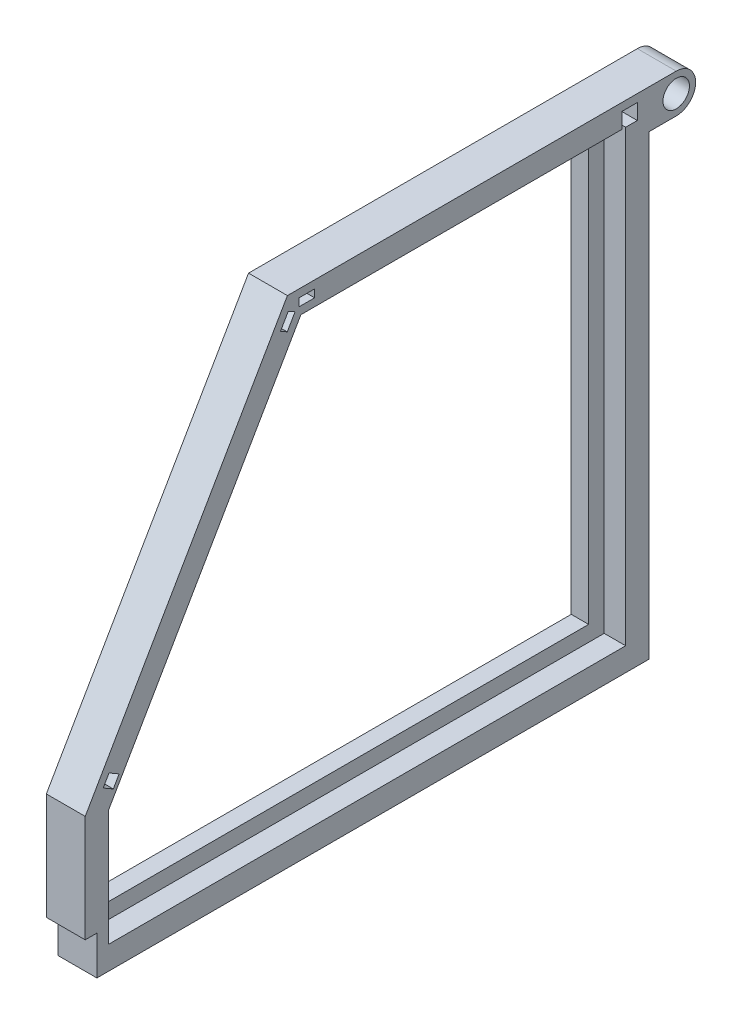
SolidWorks part; units mm, degrees
ref_plane "Front Plane" through (0, 0, 0) normal (0, 0, 1) x (1, 0, 0)
ref_plane "Top Plane" through (0, 0, 0) normal (0, 1, 0) x (1, 0, 0)
ref_plane "Right Plane" through (0, 0, 0) normal (1, 0, 0) x (0, 0, -1)
sketch "Sketch1" plane through (0, 0, 0) normal (1, 0, 0) x (0, 0, -1)
  line L0 (-36.25, 0.2437) -> (36.25, 0.2437)
  line L1 (36.25, 0.2437) -> (36.25, 58.9937)
  line L2 (36.25, 58.9937) -> (39.75, 58.9937)
  line L3 (39.75, 58.9937) -> (39.75, 61.4937) construction
  line L4 (39.75, 63.9937) -> (36.25, 63.9937)
  line L5 (36.25, 63.9937) -> (-10.25, 63.9937)
  line L6 (-36.25, 0.2437) -> (-36.25, 18.9937)
  line L7 (-36.25, 18.9937) -> (-10.25, 63.9937)
  line L8 (36.25, 0.2437) -> (31.25, 0.2437) construction
  line L9 (31.25, 0.2437) -> (31.25, 5.2437) construction
  line L12 (31.25, 5.2437) -> (-31.25, 5.2437)
  line L19 (31.25, 63.9937) -> (31.25, 58.9937) construction
  line L20 (31.25, 5.2437) -> (31.25, 58.9937)
  line L23 (-23.25, 41.4937) -> (-18.9207, 38.9924) construction
  line L24 (-18.9207, 38.9924) -> (-7.3643, 58.9937)
  line L27 (-18.9207, 38.9924) -> (-31.25, 17.6531)
  line L28 (-31.25, 5.2437) -> (-31.25, 17.6531)
  line L29 (-7.3643, 58.9937) -> (31.25, 58.9937)
  arc A0 (39.75, 58.9937) -> (39.75, 63.9937) centre (39.75, 61.4937) ccw
  point P3 (0, 0.2437)
extrude "Boss-Extrude1" add sketch "Sketch1" along normal blind 5
sketch "Sketch2" plane through (0, 0, 0) normal (-1, 0, 0) x (0, 0, 1)
  line L0 (-42.25, 61.4937) -> (-39.75, 61.4937) construction
hole_wizard "CSK for M3 Flat Head Machine Screw1" positions "Sketch3" profile "Sketch4" countersink size "M3" standard "ANSI Metric"
sketch "Sketch3" plane through (0, 0, 0) normal (-1, 0, 0) x (0, 0, 1)
  point P0 (-39.75, 61.4937)
sketch "Sketch4" plane through (0, 61.4937, -39.75) normal (0, 1, 0) x (0, 0, 1)
  line L0 (0, 0) -> (0, 11.0215)
  line L1 (0, 11.0215) -> (1.7, 10)
  line L2 (1.7, 10) -> (1.7, 0.4)
  line L3 (1.7, 0.4) -> (2.1, 0)
  line L5 (2.1, 0) -> (0, 0)
  line L6 (-1.7, 0.4) -> (-2.1, 0) construction
  line L10 (0, 11.0215) -> (-1.7, 10) construction
  line L11 (0, -6.35) -> (0, 107.95) construction
  dimension "Hole Dia." = 3.4
  dimension "Hole Depth" = 10
  dimension "Near C'Sink Dia." = 4.2
  dimension "Near C'Sink Angle" = 90
  dimension "Drill Angle" = 118
sketch "Sketch6" plane through (5, 0, 0) normal (1, 0, 0) x (0, 0, -1)
  line L0 (31.25, 58.9937) -> (31.25, 60.9937) construction
  line L1 (31.25, 60.9937) -> (33.25, 60.9937) construction
  line L2 (33.25, 60.9937) -> (33.25, 3.2437)
  line L3 (33.25, 3.2437) -> (-33.25, 3.2437)
  line L4 (-23.25, 41.4937) -> (-20.6524, 39.9929) construction
  line L7 (-31.25, 13.2412) -> (-33.25, 13.2412) construction
  line L8 (-4.0306, 58.9937) -> (-4.0306, 60.9937) construction
  line L9 (-33.25, 3.2437) -> (-33.25, 18.1894)
  line L10 (-33.25, 18.1894) -> (-8.5186, 60.9937)
  line L11 (-8.5186, 60.9937) -> (33.25, 60.9937)
extrude "Cut-Extrude1" cut sketch "Sketch6" against normal blind 2.762
sketch "Sketch9" plane through (0, 0, 36.25) normal (0, 0, 1) x (1, 0, 0)
  line L5 (5, 0.2437) -> (0, 0.2437)
  line L6 (5, 0.2437) -> (5, 5.2437)
  line L7 (5, 5.2437) -> (0, 5.2437)
  line L8 (0, 0.2437) -> (0, 5.2437)
extrude "Cut-Extrude3" cut sketch "Sketch9" against normal blind 1.5
sketch "Sketch10" plane through (5, 0, 0) normal (1, 0, 0) x (0, 0, -1)
  line L0 (36.25, 58.9937) -> (36.25, 63.9937) construction
  line L1 (36.25, 63.9937) -> (34.75, 63.9937) construction
  line L2 (34.75, 63.9937) -> (34.75, 62.9937) construction
  line L4 (34.75, 62.9937) -> (32.75, 62.9937)
  line L5 (34.75, 62.9937) -> (34.75, 60.9937)
  line L6 (34.75, 60.9937) -> (32.75, 60.9937)
  line L7 (32.75, 62.9937) -> (32.75, 60.9937)
extrude "Cut-Extrude4" cut sketch "Sketch10" against normal blind 3
sketch "Sketch13" plane through (5, 0, 0) normal (1, 0, 0) x (0, 0, -1)
  line L0 (-10.25, 63.9937) -> (-8.75, 63.9937) construction
  line L1 (-8.75, 63.9937) -> (-8.75, 62.9937) construction
  line L2 (-8.75, 62.9937) -> (-6.75, 62.9937) construction
  line L3 (-6.75, 62.9937) -> (-6.75, 60.9933) construction
  line L4 (-6.75, 60.9933) -> (-8.75, 60.9933) construction
  line L5 (-8.75, 60.9933) -> (-8.75, 62.9937) construction
  line L6 (-10.25, 63.9937) -> (-11.0004, 62.695) construction
  line L7 (-11.0004, 62.695) -> (-10.1346, 62.1947) construction
  line L8 (-10.1346, 62.1947) -> (-11.1351, 60.4629) construction
  line L9 (-11.1351, 60.4629) -> (-9.4034, 59.4624) construction
  line L10 (-9.4034, 59.4624) -> (-8.4028, 61.1941) construction
  line L11 (-8.4028, 61.1941) -> (-10.1346, 62.1947) construction
  line L12 (-9.4034, 59.4624) -> (-8.5186, 60.9937) construction
  line L13 (-10.1346, 62.1947) -> (-8.7492, 61.3942) construction
  line L14 (-8.75, 62.9937) -> (-6.75, 62.9937)
  line L19 (-11.1351, 60.4629) -> (-10.1346, 62.1947)
  line L22 (-11.1351, 60.4629) -> (-10.2692, 59.9627)
  line L23 (-10.2692, 59.9627) -> (-9.2687, 61.6944)
  line L24 (-9.2687, 61.6944) -> (-10.1346, 62.1947)
  line L25 (-8.75, 62.9937) -> (-8.75, 61.994)
  line L26 (-8.75, 61.994) -> (-6.75, 61.9937)
  line L27 (-6.75, 61.9937) -> (-6.75, 62.9937)
extrude "Cut-Extrude5" cut sketch "Sketch13" against normal blind 3
sketch "Sketch15" plane through (5, 0, 0) normal (1, 0, 0) x (0, 0, -1)
  line L0 (-36.25, 18.9937) -> (-34.0543, 22.7939) construction
  line L1 (-34.0543, 22.7939) -> (-33.1885, 22.2937) construction
  line L2 (-33.1885, 22.2937) -> (-33.9389, 20.9949)
  line L3 (-33.9389, 20.9949) -> (-32.6401, 20.2444)
  line L4 (-32.6401, 20.2444) -> (-31.8897, 21.5432)
  line L5 (-31.8897, 21.5432) -> (-33.1885, 22.2937)
extrude "Cut-Extrude6" cut sketch "Sketch15" against normal blind 3
